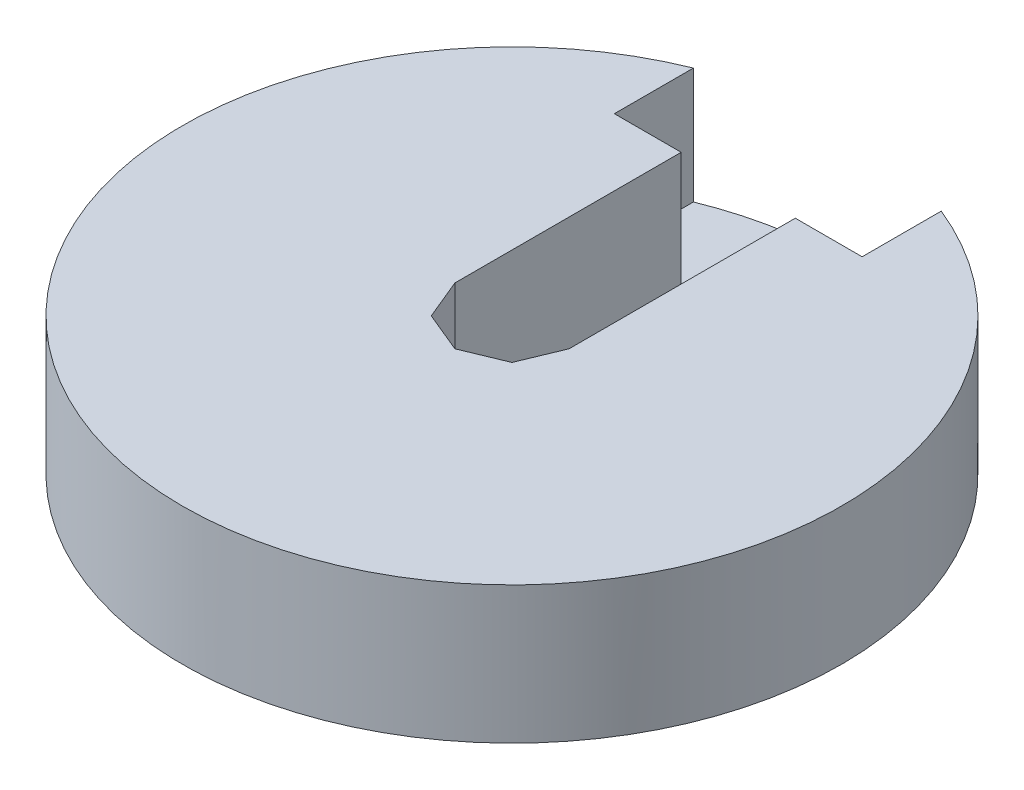
SolidWorks part; units mm, degrees
ref_plane "Front Plane" through (0, 0, 0) normal (0, 0, 1) x (1, 0, 0)
ref_plane "Top Plane" through (0, 0, 0) normal (0, 1, 0) x (1, 0, 0)
ref_plane "Right Plane" through (0, 0, 0) normal (1, 0, 0) x (0, 0, -1)
sketch "Sketch1" plane through (0, 0, 0) normal (0, 1, 0) x (1, 0, 0)
  line L8 (0, 10.8239) -> (7.6537, 7.6537)
  line L9 (7.6537, 7.6537) -> (10.8239, 0)
  line L10 (10.8239, 0) -> (7.6537, -7.6537)
  line L11 (7.6537, -7.6537) -> (0, -10.8239)
  line L12 (0, -10.8239) -> (-7.6537, -7.6537)
  line L13 (-7.6537, -7.6537) -> (-10.8239, 0)
  line L14 (-10.8239, 0) -> (-7.6537, 7.6537)
  line L15 (-7.6537, 7.6537) -> (0, 10.8239)
  line L16 (-4.7507, 8.8561) -> (-2.406, 3.1955)
  line L17 (-2.903, 9.6215) -> (-0.5582, 3.9609)
  line L18 (2.903, 9.6215) -> (0.5582, 3.9609)
  line L19 (4.7507, 8.8561) -> (2.406, 3.1955)
  line L20 (8.8561, 4.7507) -> (3.1955, 2.406)
  line L21 (9.6215, 2.903) -> (3.9609, 0.5582)
  line L22 (9.6215, -2.903) -> (3.9609, -0.5582)
  line L23 (8.8561, -4.7507) -> (3.1955, -2.406)
  line L24 (4.7507, -8.8561) -> (2.406, -3.1955)
  line L25 (2.903, -9.6215) -> (0.5582, -3.9609)
  line L26 (-2.903, -9.6215) -> (-0.5582, -3.9609)
  line L27 (-4.7507, -8.8561) -> (-2.406, -3.1955)
  line L28 (-8.8561, -4.7507) -> (-3.1955, -2.406)
  line L29 (-9.6215, -2.903) -> (-3.9609, -0.5582)
  line L30 (-9.6215, 2.903) -> (-3.9609, 0.5582)
  line L31 (-8.8561, 4.7507) -> (-3.1955, 2.406)
  circle A0 centre (0, 0) radius 4
  circle A1 centre (0, 0) radius 62.5
  circle A2 centre (0, 0) radius 10 construction
  circle A3 centre (0, 0) radius 2.5
  point P16 (-3.8268, 9.2388)
  point P20 (0, 0)
  point P21 (0, 0)
  point P50 (0, 0)
  point P51 (0.0011, 0.1832)
  point P52 (0, 0)
  point P53 (0, 0)
  point P54 (0, 0)
  dimension "D1" = 8
  dimension "D2" = 125
  dimension "D3" = 20
  dimension "D7" = 5
  dimension "D4" = 135
  dimension "D5" = 1
  dimension "D6" = 1
  dimension "D9" = 5.8059
  dimension "D8" = 8
extrude "Boss-Extrude1" add sketch "Sketch1" along normal blind 5 contours A1 L14 L15 L8 L9 L10 L11 L12 L13 | A0 A3 | A0 L23 L10 L22 | A0 L21 L9 L20 | A0 L19 L8 L18 | A0 L17 L15 L16 | A0 L31 L14 L30 | A0 L29 L13 L28 | A0 L27 L12 L26 | A0 L25 L11 L24
sketch "Sketch3" plane through (0, 5, 0) normal (0, 1, 0) x (1, 0, 0)
  line L0 (-10.8239, 0) -> (-10.8239, 42.9137)
  line L1 (10.8239, 0) -> (10.8239, 42.9137)
  line L2 (-23.5, 42.9137) -> (-23.5, 57.9137)
  line L3 (-23.5, 42.9137) -> (-10.8239, 42.9137)
  line L7 (23.5, 42.9137) -> (23.5, 57.9137)
  line L8 (-10.8239, 0) -> (-7.6537, -7.6537)
  line L9 (-7.6537, -7.6537) -> (0, -10.8239)
  line L10 (0, -10.8239) -> (7.6537, -7.6537)
  line L11 (7.6537, -7.6537) -> (10.8239, 0)
  line L12 (10.8239, 42.9137) -> (23.5, 42.9137)
  line L13 (-23.5, 57.9137) -> (23.5, 57.9137) construction
  arc A0 (-23.5, 57.9137) -> (23.5, 57.9137) centre (0, 0) ccw
  circle A1 centre (0, 0) radius 62.5 construction
  point P3 (0, 57.9137)
  dimension "D1" = 47
  dimension "D2" = 15
extrude "Boss-Extrude3" add sketch "Sketch3" along normal blind 22
sketch "Sketch4" plane through (0, 0, -42.9137) normal (0, 0, -1) x (-1, 0, 0)
  line L0 (-23.5, 27) -> (-10.8239, 27) construction
  line L1 (-23.5, 27) -> (-23.5, 5) construction
  line L3 (-10.8239, 27) -> (-10.8239, 5) construction
  line L4 (-20.5, 25.25) -> (-21.366, 24.75)
  line L5 (-21.366, 24.75) -> (-21.366, 23.75)
  line L6 (-21.366, 23.75) -> (-20.5, 23.25)
  line L7 (-20.5, 23.25) -> (-19.634, 23.75)
  line L8 (-19.634, 23.75) -> (-19.634, 24.75)
  line L9 (-19.634, 24.75) -> (-20.5, 25.25)
  line L10 (-20.5, 8.75) -> (-21.366, 8.25)
  line L11 (-21.366, 8.25) -> (-21.366, 7.25)
  line L12 (-21.366, 7.25) -> (-20.5, 6.75)
  line L13 (-20.5, 6.75) -> (-19.634, 7.25)
  line L14 (-19.634, 7.25) -> (-19.634, 8.25)
  line L15 (-19.634, 8.25) -> (-20.5, 8.75)
  line L16 (20.5, 8.75) -> (19.634, 8.25)
  line L17 (19.634, 8.25) -> (19.634, 7.25)
  line L18 (19.634, 7.25) -> (20.5, 6.75)
  line L19 (20.5, 6.75) -> (21.366, 7.25)
  line L20 (21.366, 7.25) -> (21.366, 8.25)
  line L21 (21.366, 8.25) -> (20.5, 8.75)
  line L22 (20.5, 25.25) -> (19.634, 24.75)
  line L23 (19.634, 24.75) -> (19.634, 23.75)
  line L24 (19.634, 23.75) -> (20.5, 23.25)
  line L25 (20.5, 23.25) -> (21.366, 23.75)
  line L26 (21.366, 23.75) -> (21.366, 24.75)
  line L27 (21.366, 24.75) -> (20.5, 25.25)
  circle A0 centre (-20.5, 24.25) radius 1 construction
  circle A1 centre (20.5, 24.25) radius 1 construction
  circle A2 centre (20.5, 7.75) radius 1 construction
  circle A3 centre (-20.5, 7.75) radius 1 construction
  circle A4 centre (-20.5, 24.25) radius 0.866 construction
  circle A5 centre (-20.5, 7.75) radius 0.866 construction
  circle A6 centre (20.5, 7.75) radius 0.866 construction
  circle A7 centre (20.5, 24.25) radius 0.866 construction
  point P42 (0, 0)
  point P43 (0, 0)
  point P44 (0, 0)
  point P45 (0, 0)
  dimension "D1" = 2
  dimension "D3" = 3
  dimension "D6" = 16.5
  dimension "D7" = 41
  dimension "D8" = 41
  dimension "D2" = 2.75
  dimension "D4" = 2
  dimension "D5" = 2
extrude "Cut-Extrude1" cut sketch "Sketch4" against normal blind 20
ref_plane "Plane1" through (0, 0, -62.5) normal (0, 0, -1) x (-1, 0, 0)
sketch "Sketch7" plane through (0, 0, -62.5) normal (0, 0, -1) x (-1, 0, 0)
  line L9 (-7.5, 4) -> (7.5, 4)
  line L10 (7.5, 4) -> (7.5, 2)
  line L11 (7.5, 2) -> (1.5, 2)
  line L12 (1.5, 2) -> (1.5, 0)
  line L13 (1.5, 0) -> (-1.5, 0)
  line L15 (-1.5, 0) -> (-1.5, 2)
  line L16 (-1.5, 2) -> (-7.5, 2)
  line L17 (-7.5, 2) -> (-7.5, 4)
  line L18 (-62.5, 0) -> (62.5, 0) construction
  point P2 (0, 0)
  point P12 (-2.5963, -1.04)
  dimension "D1" = 3
  dimension "D2" = 15
  dimension "D3" = 2
  dimension "D4" = 2
extrude "Cut-Extrude2" cut sketch "Sketch7" against normal blind 11
sketch "Sketch8" plane through (0, 0, 0) normal (0, -1, 0) x (1, 0, 0)
  line L0 (-1.5, -51.5) -> (-1.5, -62.482) construction
  line L1 (1.5, -51.5) -> (1.5, -62.482) construction
  circle A0 centre (-4, -57) radius 1
  circle A1 centre (4, -57) radius 1
  point P8 (0, 0)
  dimension "D1" = 2
  dimension "D2" = 2.5
  dimension "D3" = 2.5
  dimension "D4" = 5.5
extrude "Cut-Extrude3" cut sketch "Sketch8" against normal up to surface (5 mm away)
sketch "Sketch11" plane through (0, 0, 0) normal (0, -1, 0) x (1, 0, 0)
  circle A0 centre (0, 0) radius 12.5
  circle A1 centre (0, 0) radius 62.5
  arc A2 (1.5, -62.482) -> (-1.5, -62.482) centre (0, 0) ccw construction
  dimension "D1" = 25
extrude "Cut-Extrude6" cut sketch "Sketch11" against normal blind 1
